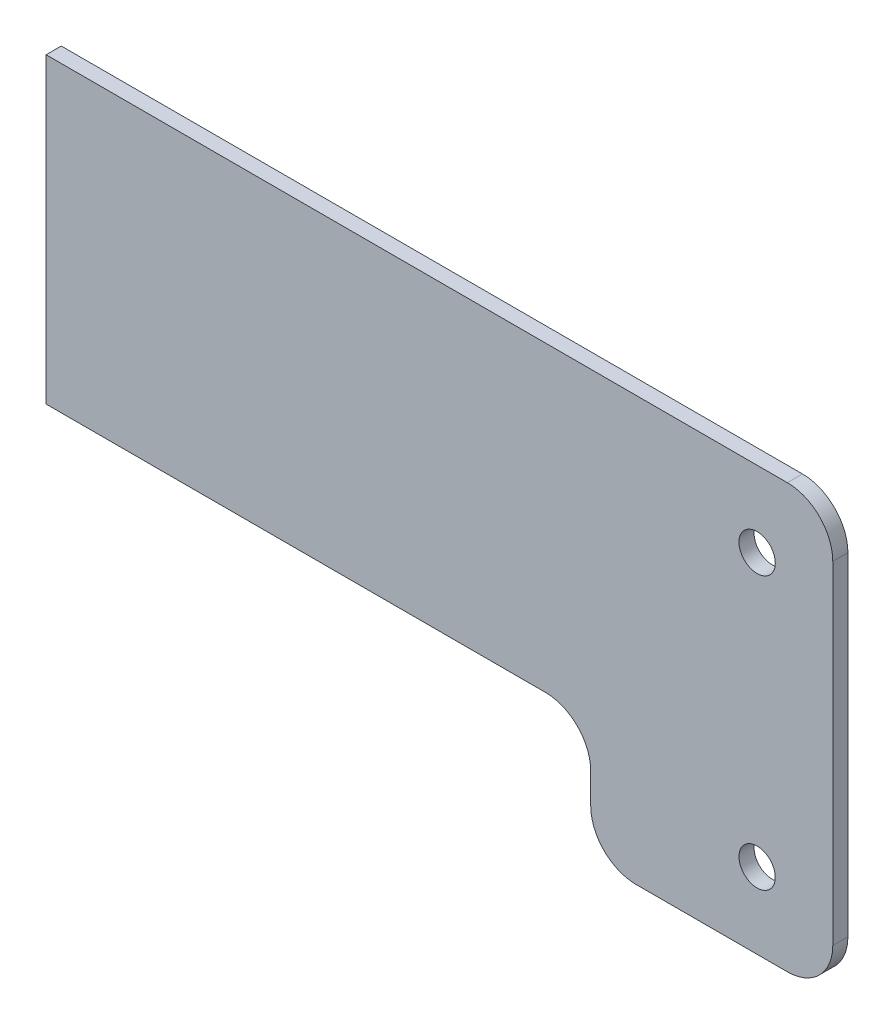
SolidWorks part; units mm, degrees
ref_plane "Front Plane" through (0, 0, 0) normal (0, 0, 1) x (1, 0, 0)
ref_plane "Top Plane" through (0, 0, 0) normal (0, 1, 0) x (1, 0, 0)
ref_plane "Right Plane" through (0, 0, 0) normal (1, 0, 0) x (0, 0, -1)
sketch "Sketch1" plane through (0, 0, 0) normal (0, 0, 1) x (1, 0, 0)
  line L0 (-38.8505, 0) -> (78.8565, 0) construction
  line L1 (0, -55.4937) -> (0, 61.9815) construction
  line L2 (-122.5, 70) -> (122.5, 70)
  line L3 (137.5, 55) -> (137.5, -55)
  line L4 (112.5, 39) -> (112.5, -39) construction
  line L5 (-122.5, 70) -> (-122.5, -30)
  line L6 (-122.5, -30) -> (42.5, -30)
  line L7 (57.5, -45) -> (57.5, -55)
  line L8 (72.5, -70) -> (122.5, -70)
  circle A0 centre (112.5, 45) radius 6
  circle A1 centre (112.5, -45) radius 6
  arc A2 (137.5, -55) -> (122.5, -70) centre (122.5, -55) cw
  arc A3 (122.5, 70) -> (137.5, 55) centre (122.5, 55) cw
  arc A4 (57.5, -55) -> (72.5, -70) centre (72.5, -55) ccw
  arc A5 (42.5, -30) -> (57.5, -45) centre (42.5, -45) cw
  point P7 (0, 70)
  point P9 (137.5, 0)
  point P21 (137.5, -70)
  point P26 (57.5, -70)
  point P29 (57.5, -30)
  dimension "D1" = 12
  dimension "D2" = 25
  dimension "D3" = 25
  dimension "D8" = 15
  dimension "D4" = 260
  dimension "D5" = 100
  dimension "D6" = 40
  dimension "D7" = 80
extrude "Boss-Extrude1" add sketch "Sketch1" along normal mid plane 5
